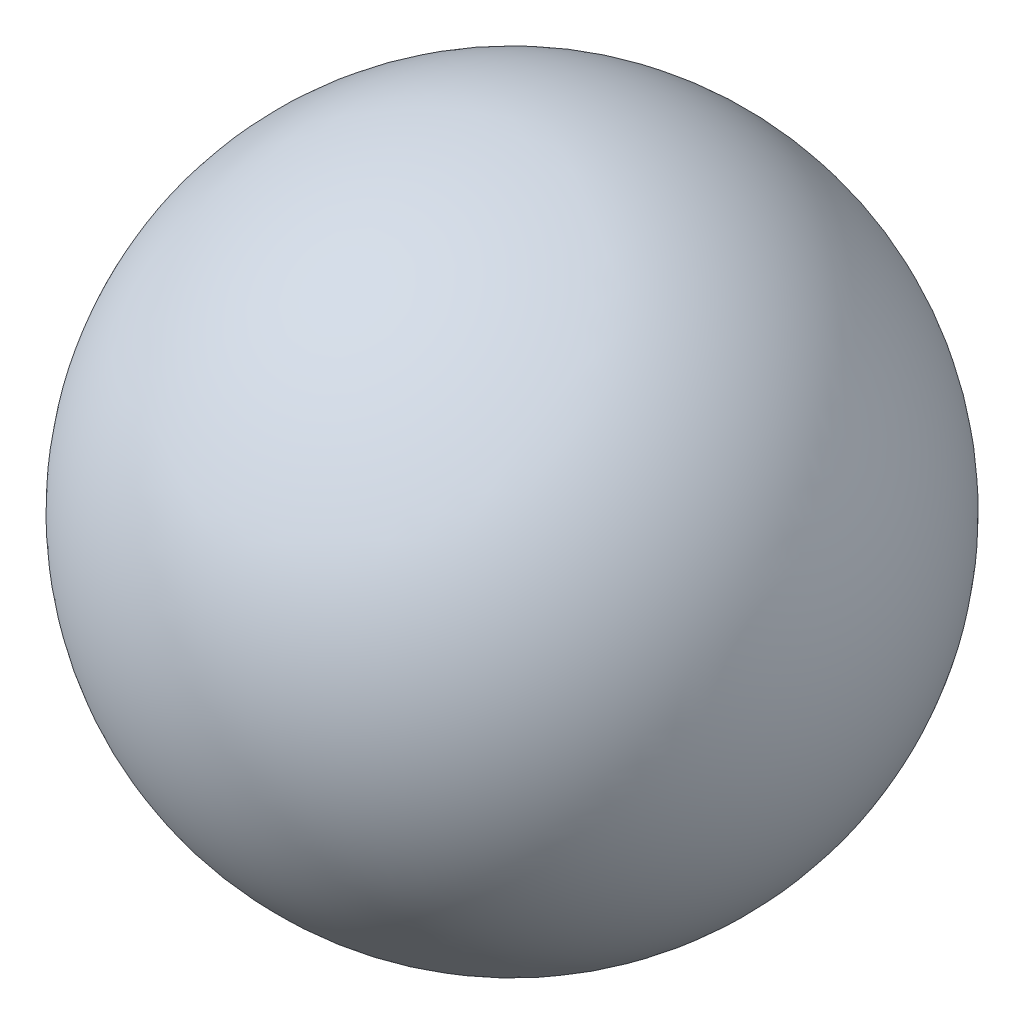
SolidWorks part; units mm, degrees
ref_plane "前视基准面" through (0, 0, 0) normal (0, 0, 1) x (1, 0, 0)
ref_plane "上视基准面" through (0, 0, 0) normal (0, 1, 0) x (1, 0, 0)
ref_plane "右视基准面" through (0, 0, 0) normal (1, 0, 0) x (0, 0, -1)
other "Configuration Table"
sketch "草图1" plane through (0, 0, 0) normal (0, 0, 1) x (1, 0, 0)
  line L0 (0, 0) -> (13, 0) construction
  line L1 (0, 0) -> (-44.9894, 0) construction
  line L2 (13, 0) -> (-13, 0)
  arc A0 (13, 0) -> (-13, 0) centre (0, 0) ccw
  dimension "D1" = 13
revolve "旋转6" add sketch "草图1" angle 360 about L2
